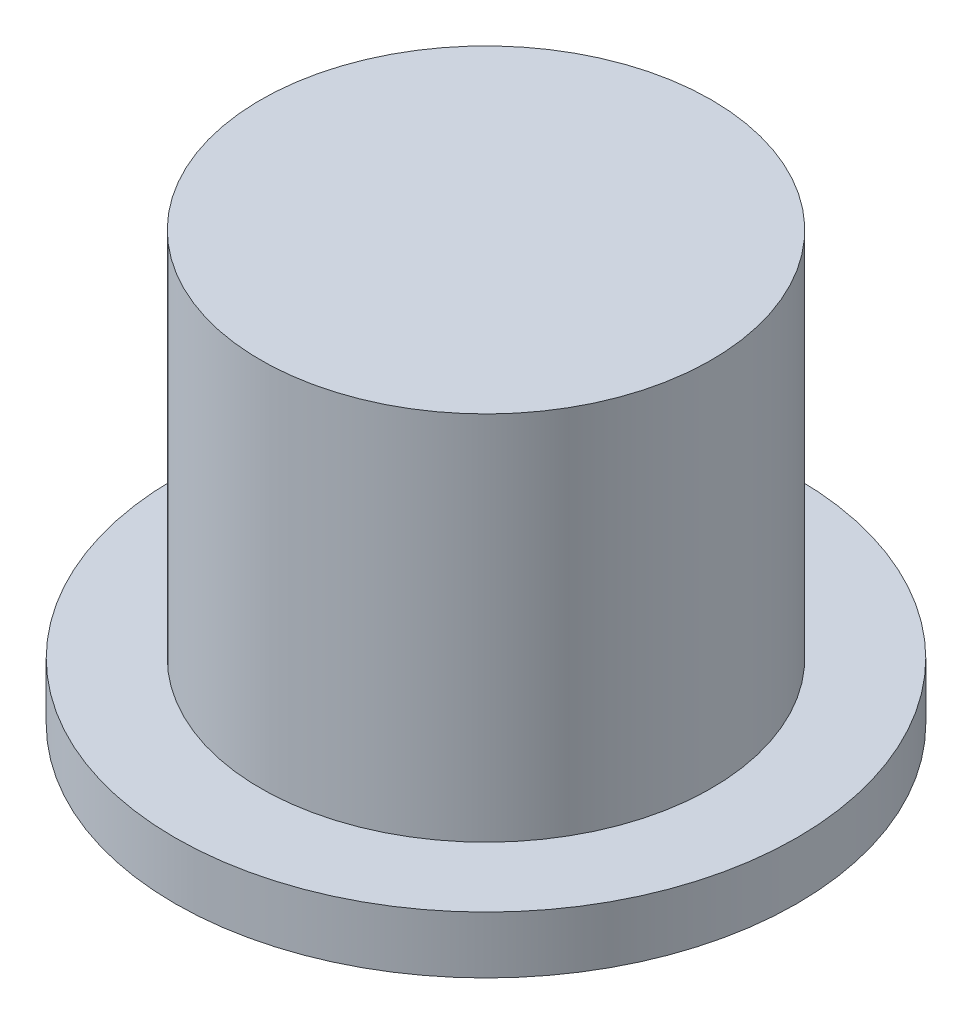
SolidWorks part; units mm, degrees
ref_plane "Front Plane" through (0, 0, 0) normal (0, 0, 1) x (1, 0, 0)
ref_plane "Top Plane" through (0, 0, 0) normal (0, 1, 0) x (1, 0, 0)
ref_plane "Right Plane" through (0, 0, 0) normal (1, 0, 0) x (0, 0, -1)
sketch "Sketch2" plane through (0, 0, 0) normal (0, 1, 0) x (1, 0, 0)
  circle A0 centre (0, 0) radius 3.95
  dimension "D1" = 7.9
extrude "Boss-Extrude1" add sketch "Sketch2" along normal mid plane 6.5
ref_plane "Plane1" through (0, 2.25, 0) normal (0, 1, 0) x (1, 0, 0)
sketch "Sketch5" plane through (0, -3.25, 0) normal (0, -1, 0) x (1, 0, 0)
  circle A0 centre (0, 0) radius 3.5
  dimension "D1" = 7
extrude "Boss-Extrude4" add sketch "Sketch5" along normal blind 2
sketch "Sketch7" plane through (0, -3.25, 0) normal (0, -1, 0) x (1, 0, 0)
  circle A0 centre (0, 0) radius 5.45
  circle A1 centre (0, 0) radius 3.95 construction
  dimension "D1" = 1.5
extrude "Boss-Extrude5" add sketch "Sketch7" along normal blind 1
sketch "Sketch6" plane through (0, -5.25, 0) normal (0, -1, 0) x (1, 0, 0)
  line L0 (-1.4595, -1.475) -> (1.4595, -1.475)
  circle A0 centre (0, 0) radius 2.075
  point P5 (0, 2.075)
  dimension "D2" = 4.15
  dimension "D1" = 3.55
extrude "Cut-Extrude1" cut sketch "Sketch6" against normal blind 8.1 contours L0 A0
